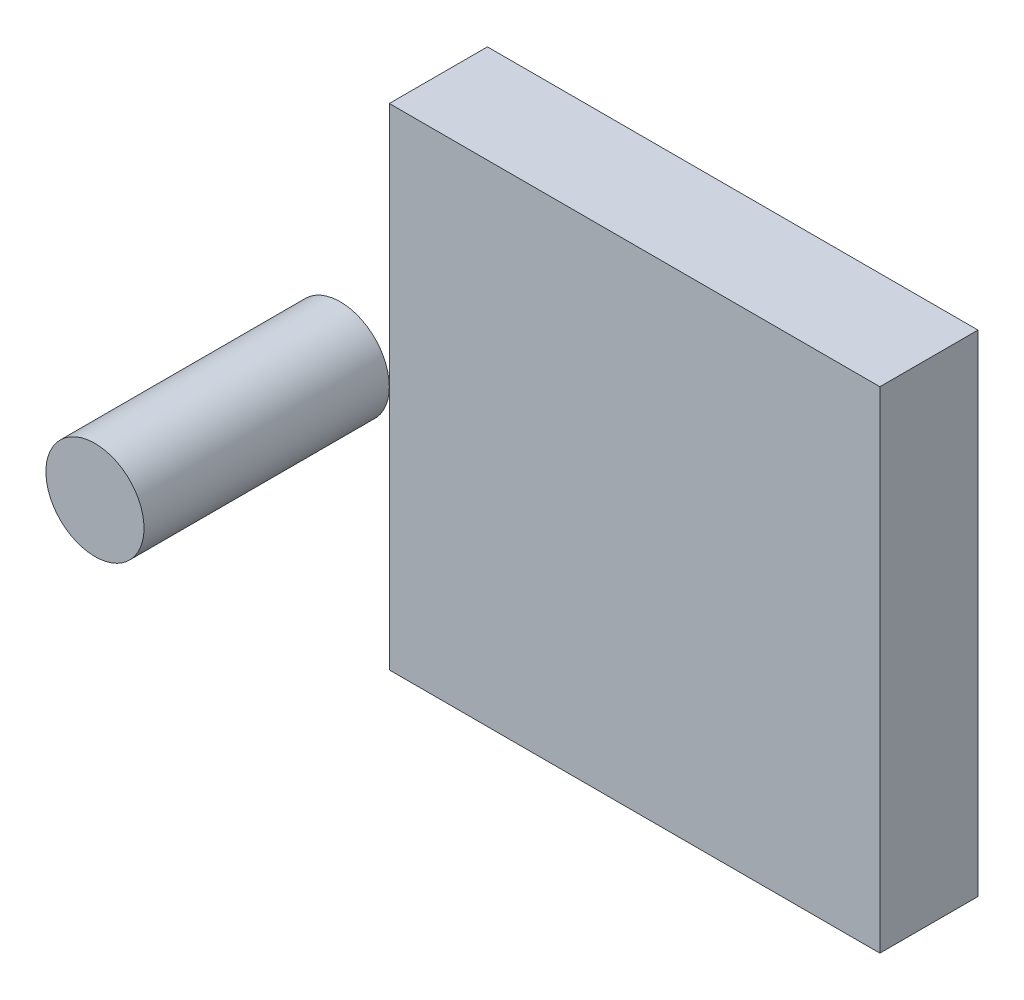
SolidWorks part; units mm, degrees
ref_plane "前视基准面" through (0, 0, 0) normal (0, 0, 1) x (1, 0, 0)
ref_plane "上视基准面" through (0, 0, 0) normal (0, 1, 0) x (1, 0, 0)
ref_plane "右视基准面" through (0, 0, 0) normal (1, 0, 0) x (0, 0, -1)
other "Configuration Table"
sketch "草图1" plane through (0, 0, 0) normal (0, 0, 1) x (1, 0, 0)
  line L1 (-50, -50) -> (50, -50)
  line L2 (-50, -50) -> (-50, 50)
  line L3 (-50, 50) -> (50, 50)
  line L4 (50, -50) -> (50, 50)
  line L5 (-50, -50) -> (50, 50) construction
  line L6 (-50, 50) -> (50, -50) construction
  point P0 (0, 0)
extrude "凸台-拉伸1" add sketch "草图1" along normal blind 20
sketch "草图2" plane through (0, 0, 20) normal (0, 0, 1) x (1, 0, 0)
  circle A0 centre (-60, 0) radius 10
extrude "凸台-拉伸2" add sketch "草图2" along normal blind 50
